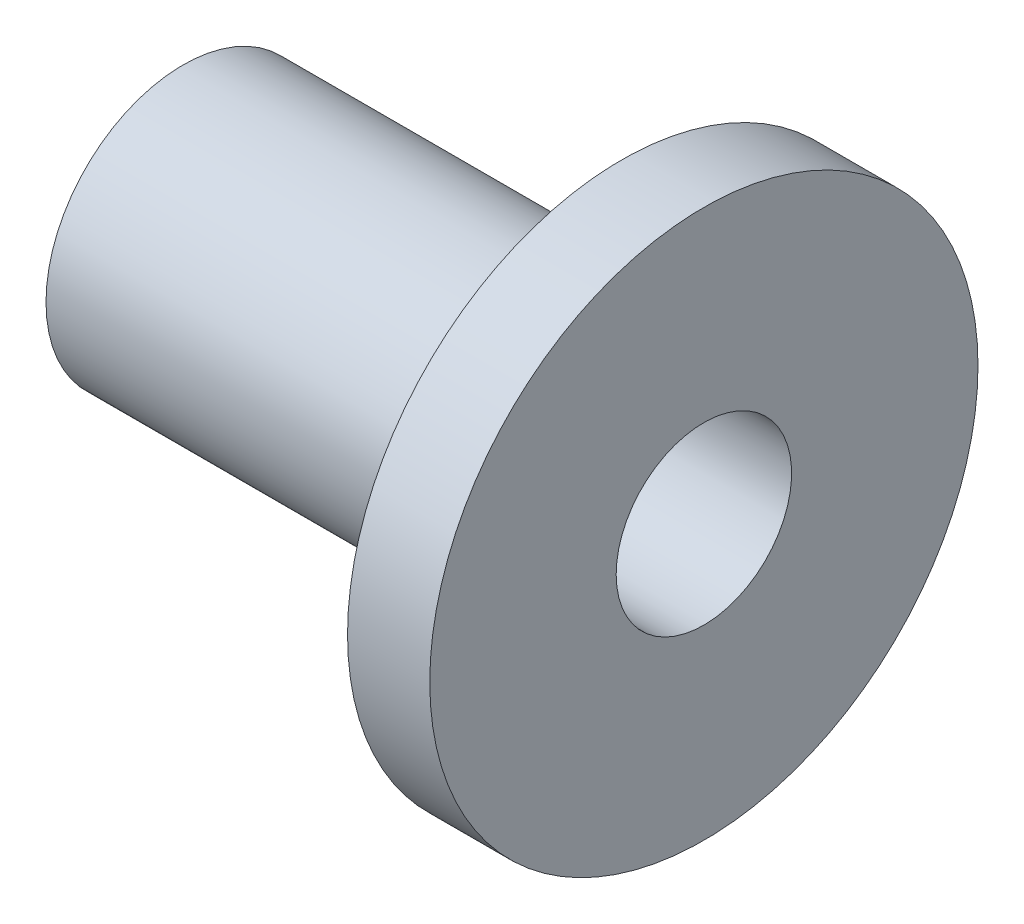
SolidWorks part; units mm, degrees
ref_plane "前视基准面" through (0, 0, 0) normal (0, 0, 1) x (1, 0, 0)
ref_plane "上视基准面" through (0, 0, 0) normal (0, 1, 0) x (1, 0, 0)
ref_plane "右视基准面" through (0, 0, 0) normal (1, 0, 0) x (0, 0, -1)
other "Configuration Table"
sketch "草图1" plane through (0, 0, 0) normal (0, 0, 1) x (1, 0, 0)
  line L0 (0, 0) -> (9.5, 0)
  line L1 (9.5, 1.6) -> (9.5, 5)
  line L2 (9.5, 5) -> (8, 5)
  line L3 (0, 1.6) -> (0, 2.5)
  line L4 (0, 2.5) -> (8, 2.5)
  line L5 (8, 2.5) -> (8, 5)
  line L6 (0, 1.6) -> (9.5, 1.6)
  dimension "D1" = 1.5
  dimension "D2" = 2.5
  dimension "D3" = 8
  dimension "D4" = 2.5
  dimension "D5" = 1.6
revolve "旋转1" add sketch "草图1" angle 360 about L0
